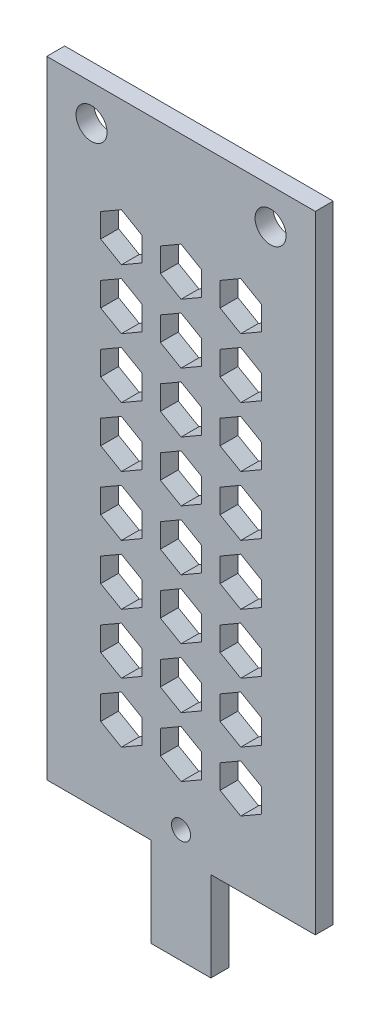
SolidWorks part; units mm, degrees
ref_plane "前视基准面" through (0, 0, 0) normal (0, 0, 1) x (1, 0, 0)
ref_plane "上视基准面" through (0, 0, 0) normal (0, 1, 0) x (1, 0, 0)
ref_plane "右视基准面" through (0, 0, 0) normal (1, 0, 0) x (0, 0, -1)
other "Configuration Table"
sketch "草图2" plane through (0, 0, 0) normal (0, 0, 1) x (1, 0, 0)
  line L0 (0, -41) -> (0, 0) construction
  line L1 (22.5, -60) -> (-22.5, -60)
  line L2 (22.5, -60) -> (22.5, 60)
  line L3 (22.5, 60) -> (-22.5, 60)
  line L4 (-22.5, -60) -> (-22.5, 60)
  line L5 (22.5, -60) -> (-22.5, 60) construction
  line L6 (22.5, 60) -> (-22.5, -60) construction
  line L7 (10, 4) -> (6.5359, 2)
  line L8 (0, 4) -> (-3.4641, 2)
  line L9 (-3.4641, 2) -> (-3.4641, -2)
  line L10 (-3.4641, -2) -> (0, -4)
  line L11 (0, -4) -> (3.4641, -2)
  line L12 (3.4641, -2) -> (3.4641, 2)
  line L13 (3.4641, 2) -> (0, 4)
  line L14 (6.5359, 2) -> (6.5359, -2)
  line L15 (6.5359, -2) -> (10, -4)
  line L16 (10, -4) -> (13.4641, -2)
  line L17 (13.4641, -2) -> (13.4641, 2)
  line L18 (13.4641, 2) -> (10, 4)
  line L19 (-10, 4) -> (-13.4641, 2)
  line L20 (-13.4641, 2) -> (-13.4641, -2)
  line L21 (-13.4641, -2) -> (-10, -4)
  line L22 (-10, -4) -> (-6.5359, -2)
  line L23 (-6.5359, -2) -> (-6.5359, 2)
  line L24 (-6.5359, 2) -> (-10, 4)
  line L25 (10, 14) -> (6.5359, 12)
  line L26 (6.5359, 12) -> (6.5359, 8)
  line L27 (6.5359, 8) -> (10, 6)
  line L28 (10, 6) -> (13.4641, 8)
  line L29 (13.4641, 8) -> (13.4641, 12)
  line L30 (13.4641, 12) -> (10, 14)
  line L31 (0, 14) -> (-3.4641, 12)
  line L32 (-3.4641, 12) -> (-3.4641, 8)
  line L33 (-3.4641, 8) -> (0, 6)
  line L34 (0, 6) -> (3.4641, 8)
  line L35 (3.4641, 8) -> (3.4641, 12)
  line L36 (3.4641, 12) -> (0, 14)
  line L37 (-10, 14) -> (-13.4641, 12)
  line L38 (-13.4641, 12) -> (-13.4641, 8)
  line L39 (-13.4641, 8) -> (-10, 6)
  line L40 (-10, 6) -> (-6.5359, 8)
  line L41 (-6.5359, 8) -> (-6.5359, 12)
  line L42 (-6.5359, 12) -> (-10, 14)
  line L43 (10, 24) -> (6.5359, 22)
  line L44 (6.5359, 22) -> (6.5359, 18)
  line L45 (6.5359, 18) -> (10, 16)
  line L46 (10, 16) -> (13.4641, 18)
  line L47 (13.4641, 18) -> (13.4641, 22)
  line L48 (13.4641, 22) -> (10, 24)
  line L49 (0, 24) -> (-3.4641, 22)
  line L50 (-3.4641, 22) -> (-3.4641, 18)
  line L51 (-3.4641, 18) -> (0, 16)
  line L52 (0, 16) -> (3.4641, 18)
  line L53 (3.4641, 18) -> (3.4641, 22)
  line L54 (3.4641, 22) -> (0, 24)
  line L55 (-10, 24) -> (-13.4641, 22)
  line L56 (-13.4641, 22) -> (-13.4641, 18)
  line L57 (-13.4641, 18) -> (-10, 16)
  line L58 (-10, 16) -> (-6.5359, 18)
  line L59 (-6.5359, 18) -> (-6.5359, 22)
  line L60 (-6.5359, 22) -> (-10, 24)
  line L61 (10, 34) -> (6.5359, 32)
  line L62 (6.5359, 32) -> (6.5359, 28)
  line L63 (6.5359, 28) -> (10, 26)
  line L64 (10, 26) -> (13.4641, 28)
  line L65 (13.4641, 28) -> (13.4641, 32)
  line L66 (13.4641, 32) -> (10, 34)
  line L67 (0, 34) -> (-3.4641, 32)
  line L68 (-3.4641, 32) -> (-3.4641, 28)
  line L69 (-3.4641, 28) -> (0, 26)
  line L70 (0, 26) -> (3.4641, 28)
  line L71 (3.4641, 28) -> (3.4641, 32)
  line L72 (3.4641, 32) -> (0, 34)
  line L73 (-10, 34) -> (-13.4641, 32)
  line L74 (-13.4641, 32) -> (-13.4641, 28)
  line L75 (-13.4641, 28) -> (-10, 26)
  line L76 (-10, 26) -> (-6.5359, 28)
  line L77 (-6.5359, 28) -> (-6.5359, 32)
  line L78 (-6.5359, 32) -> (-10, 34)
  line L79 (10, 44) -> (6.5359, 42)
  line L80 (6.5359, 42) -> (6.5359, 38)
  line L81 (6.5359, 38) -> (10, 36)
  line L82 (10, 36) -> (13.4641, 38)
  line L83 (13.4641, 38) -> (13.4641, 42)
  line L84 (13.4641, 42) -> (10, 44)
  line L85 (0, 44) -> (-3.4641, 42)
  line L86 (-3.4641, 42) -> (-3.4641, 38)
  line L87 (-3.4641, 38) -> (0, 36)
  line L88 (0, 36) -> (3.4641, 38)
  line L89 (3.4641, 38) -> (3.4641, 42)
  line L90 (3.4641, 42) -> (0, 44)
  line L91 (-10, 44) -> (-13.4641, 42)
  line L92 (-13.4641, 42) -> (-13.4641, 38)
  line L93 (-13.4641, 38) -> (-10, 36)
  line L94 (-10, 36) -> (-6.5359, 38)
  line L95 (-6.5359, 38) -> (-6.5359, 42)
  line L96 (-6.5359, 42) -> (-10, 44)
  line L97 (-10, -6) -> (-13.4641, -8)
  line L98 (-13.4641, -8) -> (-13.4641, -12)
  line L99 (-13.4641, -12) -> (-10, -14)
  line L100 (-10, -14) -> (-6.5359, -12)
  line L101 (-6.5359, -12) -> (-6.5359, -8)
  line L102 (-6.5359, -8) -> (-10, -6)
  line L103 (0, -6) -> (-3.4641, -8)
  line L104 (-3.4641, -8) -> (-3.4641, -12)
  line L105 (-3.4641, -12) -> (0, -14)
  line L106 (0, -14) -> (3.4641, -12)
  line L107 (3.4641, -12) -> (3.4641, -8)
  line L108 (3.4641, -8) -> (0, -6)
  line L109 (10, -6) -> (6.5359, -8)
  line L110 (6.5359, -8) -> (6.5359, -12)
  line L111 (6.5359, -12) -> (10, -14)
  line L112 (10, -14) -> (13.4641, -12)
  line L113 (13.4641, -12) -> (13.4641, -8)
  line L114 (13.4641, -8) -> (10, -6)
  line L115 (-10, -16) -> (-13.4641, -18)
  line L116 (-13.4641, -18) -> (-13.4641, -22)
  line L117 (-13.4641, -22) -> (-10, -24)
  line L118 (-10, -24) -> (-6.5359, -22)
  line L119 (-6.5359, -22) -> (-6.5359, -18)
  line L120 (-6.5359, -18) -> (-10, -16)
  line L121 (0, -16) -> (-3.4641, -18)
  line L122 (-3.4641, -18) -> (-3.4641, -22)
  line L123 (-3.4641, -22) -> (0, -24)
  line L124 (0, -24) -> (3.4641, -22)
  line L125 (3.4641, -22) -> (3.4641, -18)
  line L126 (3.4641, -18) -> (0, -16)
  line L127 (10, -16) -> (6.5359, -18)
  line L128 (6.5359, -18) -> (6.5359, -22)
  line L129 (6.5359, -22) -> (10, -24)
  line L130 (10, -24) -> (13.4641, -22)
  line L131 (13.4641, -22) -> (13.4641, -18)
  line L132 (13.4641, -18) -> (10, -16)
  line L133 (-10, -26) -> (-13.4641, -28)
  line L134 (-13.4641, -28) -> (-13.4641, -32)
  line L135 (-13.4641, -32) -> (-10, -34)
  line L136 (-10, -34) -> (-6.5359, -32)
  line L137 (-6.5359, -32) -> (-6.5359, -28)
  line L138 (-6.5359, -28) -> (-10, -26)
  line L139 (0, -26) -> (-3.4641, -28)
  line L140 (-3.4641, -28) -> (-3.4641, -32)
  line L141 (-3.4641, -32) -> (0, -34)
  line L142 (0, -34) -> (3.4641, -32)
  line L143 (3.4641, -32) -> (3.4641, -28)
  line L144 (3.4641, -28) -> (0, -26)
  line L145 (10, -26) -> (6.5359, -28)
  line L146 (6.5359, -28) -> (6.5359, -32)
  line L147 (6.5359, -32) -> (10, -34)
  line L148 (10, -34) -> (13.4641, -32)
  line L149 (13.4641, -32) -> (13.4641, -28)
  line L150 (13.4641, -28) -> (10, -26)
  circle A0 centre (-15, 54) radius 2.6
  circle A1 centre (15, 54) radius 2.6
  circle A2 centre (0, -41) radius 1.6
  circle A3 centre (0, 0) radius 3.4641 construction
  point P0 (0, 0)
  dimension "D3" = 5.2
  dimension "D8" = 3.2
  dimension "D1" = 120
  dimension "D2" = 45
  dimension "D4" = 15
  dimension "D5" = 15
  dimension "D6" = 54
  dimension "D7" = 54
  dimension "D9" = 19
  dimension "D10" = 4
  dimension "D13" = 10
  dimension "D14" = 10
  dimension "D11" = 2
  dimension "D12" = 2
  dimension "D15" = 5
  dimension "D16" = 4
extrude "凸台-拉伸1" add sketch "草图2" along normal blind 3
sketch "草图3" plane through (0, 0, 3) normal (0, 0, 1) x (1, 0, 0)
  line L0 (-22.5, -60) -> (22.5, -60) construction
  line L1 (-5, -60) -> (-22.5, -60)
  line L2 (-5, -60) -> (-5, -45)
  line L3 (-5, -45) -> (-22.5, -45)
  line L4 (-22.5, -60) -> (-22.5, -45)
  line L5 (-22.5, 60) -> (-22.5, -60) construction
  line L6 (22.5, -60) -> (22.5, 60) construction
  line L7 (5, -60) -> (22.5, -60)
  line L8 (5, -60) -> (5, -45)
  line L9 (5, -45) -> (22.5, -45)
  line L10 (22.5, -60) -> (22.5, -45)
  dimension "D1" = 10
  dimension "D2" = 15
extrude "切除-拉伸1" cut sketch "草图3" against normal up to surface (3 mm away) up to face at (-10, -30, 0)
